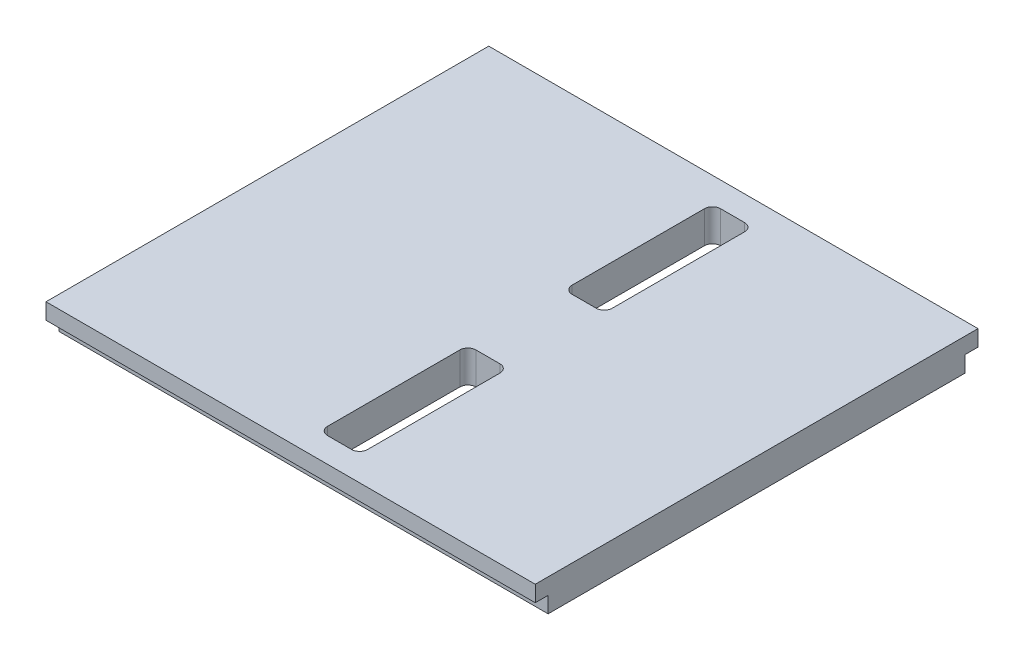
SolidWorks part; units mm, degrees
material "PE High Density"
ref_plane "Front Plane" through (0, 0, 0) normal (0, 0, 1) x (1, 0, 0)
ref_plane "Top Plane" through (0, 0, 0) normal (0, 1, 0) x (1, 0, 0)
ref_plane "Right Plane" through (0, 0, 0) normal (1, 0, 0) x (0, 0, -1)
sketch "Sketch1" plane through (0, 0, 0) normal (1, 0, 0) x (0, 0, -1)
  line L1 (-87.63, -6.35) -> (87.63, -6.35)
  line L2 (-87.63, -6.35) -> (-87.63, 6.35)
  line L3 (-87.63, 6.35) -> (87.63, 6.35)
  line L4 (87.63, -6.35) -> (87.63, 6.35)
  line L5 (-87.63, -6.35) -> (87.63, 6.35) construction
  line L6 (-87.63, 6.35) -> (87.63, -6.35) construction
  point P0 (0, 0)
  dimension "D1" = 175.26
  dimension "D2" = 12.7
extrude "Boss-Extrude1" add sketch "Sketch1" along normal mid plane 193.675
sketch "Sketch2" plane through (96.8375, 0, 0) normal (1, 0, 0) x (0, 0, -1)
  line L0 (87.63, 6.35) -> (-87.63, 6.35) construction
  line L1 (-87.63, -6.35) -> (-82.55, -6.35)
  line L2 (-87.63, -6.35) -> (-87.63, 0)
  line L3 (-87.63, 0) -> (-82.55, 0)
  line L4 (-82.55, -6.35) -> (-82.55, 0)
  line L5 (87.63, -6.35) -> (82.55, -6.35)
  line L6 (87.63, -6.35) -> (87.63, 0)
  line L7 (87.63, 0) -> (82.55, 0)
  line L8 (82.55, -6.35) -> (82.55, 0)
  dimension "D1" = 6.35
  dimension "D2" = 165.1
extrude "Cut-Extrude1" cut sketch "Sketch2" against normal through all
sketch "Sketch3" plane through (0, -6.35, 0) normal (0, 1, 0) x (1, 0, 0)
  line L0 (96.8375, 87.63) -> (96.8375, -87.63) construction
  line L1 (28.448, 11.2395) -> (41.402, 11.2395)
  line L2 (28.448, 4.6355) -> (28.448, -4.6355)
  line L3 (28.448, -11.2395) -> (41.402, -11.2395)
  line L4 (41.402, 4.6355) -> (41.402, -4.6355)
  line L5 (-22.352, 11.2395) -> (-9.398, 11.2395)
  line L6 (-9.398, 4.6355) -> (-9.398, -4.6355)
  line L7 (-22.352, -11.2395) -> (-9.398, -11.2395)
  line L8 (-22.352, 4.6355) -> (-22.352, -4.6355)
  line L17 (28.448, 11.2395) -> (-22.352, 11.2395) construction
  arc A0 (28.448, 11.2395) -> (28.448, 4.6355) centre (28.448, 7.9375) ccw
  arc A1 (28.448, -4.6355) -> (28.448, -11.2395) centre (28.448, -7.9375) ccw
  arc A2 (41.402, -11.2395) -> (41.402, -4.6355) centre (41.402, -7.9375) ccw
  arc A3 (41.402, 4.6355) -> (41.402, 11.2395) centre (41.402, 7.9375) ccw
  arc A4 (-9.398, 4.6355) -> (-9.398, 11.2395) centre (-9.398, 7.9375) ccw
  arc A5 (-9.398, -11.2395) -> (-9.398, -4.6355) centre (-9.398, -7.9375) ccw
  arc A6 (-22.352, -4.6355) -> (-22.352, -11.2395) centre (-22.352, -7.9375) ccw
  arc A7 (-22.352, 11.2395) -> (-22.352, 4.6355) centre (-22.352, 7.9375) ccw
  point P11 (34.925, 11.2395)
  point P15 (41.402, 0)
  point P16 (96.8375, 0)
  dimension "D3" = 6.604
  dimension "D1" = 12.954
  dimension "D2" = 22.479
  dimension "D4" = 61.9125
  dimension "D8" = 50.8
  dimension "D6" = 2
  dimension "D7" = 1
extrude "Cut-Extrude2" cut sketch "Sketch3" along normal blind 6.35
sketch "Sketch5" plane through (0, 6.35, 0) normal (0, 1, 0) x (1, 0, 0)
  line L0 (96.8375, 87.63) -> (96.8375, -87.63) construction
  line L1 (17.4625, -77.7875) -> (1.5875, -77.7875)
  line L2 (17.4625, -77.7875) -> (17.4625, -19.05)
  line L3 (17.4625, -19.05) -> (1.5875, -19.05)
  line L4 (1.5875, -77.7875) -> (1.5875, -19.05)
  line L5 (17.4625, -77.7875) -> (1.5875, -19.05) construction
  line L6 (17.4625, -19.05) -> (1.5875, -77.7875) construction
  line L7 (17.4625, 77.7875) -> (1.5875, 77.7875)
  line L8 (17.4625, 77.7875) -> (17.4625, 19.05)
  line L9 (17.4625, 19.05) -> (1.5875, 19.05)
  line L10 (1.5875, 77.7875) -> (1.5875, 19.05)
  line L11 (17.4625, 77.7875) -> (1.5875, 19.05) construction
  line L12 (17.4625, 19.05) -> (1.5875, 77.7875) construction
  point P0 (9.525, -48.4187)
  point P5 (9.525, 48.4187)
  point P12 (96.8375, 0)
  dimension "D1" = 15.875
  dimension "D2" = 58.7375
  dimension "D3" = 96.8375
  dimension "D4" = 48.4187
  dimension "D5" = 87.3125
extrude "Cut-Extrude4" cut sketch "Sketch5" against normal through all
fillet "Fillet1" radius 3.175 8 edges at (17.4625, 0, -19.05) (17.4625, 0, -77.7875) (1.5875, 0, -77.7875) (1.5875, 0, -19.05) (17.4625, 0, 77.7875) (17.4625, 0, 19.05) (1.5875, 0, 19.05) (1.5875, 0, 77.7875)
equation "\"D1@Boss-Extrude1\"=7.66629343in "
equation "\"D4@Sketch5\"=\"D3@Sketch5\"/2"
